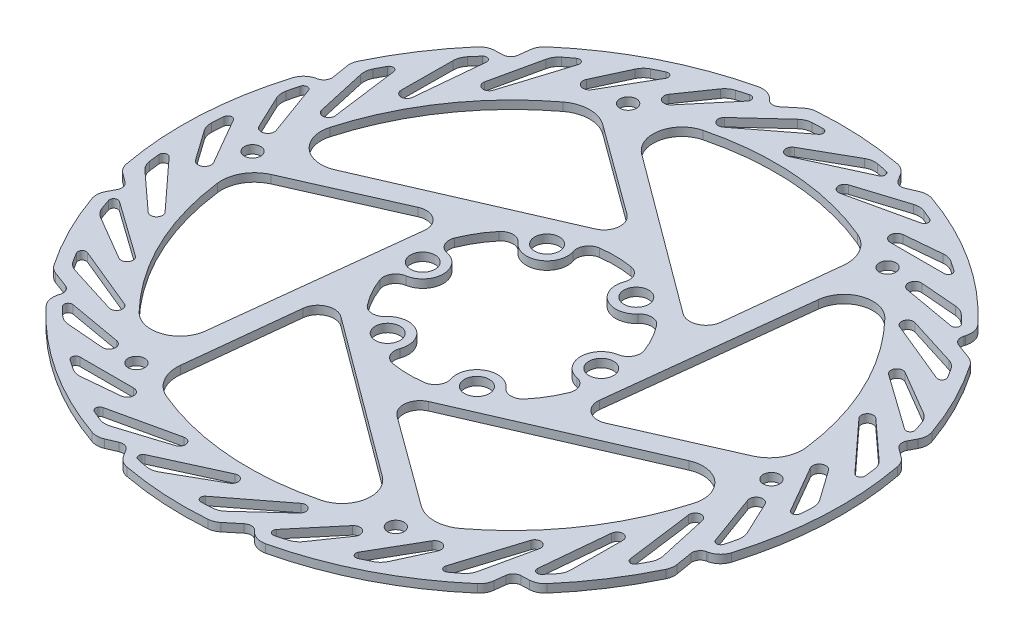
SolidWorks part; units mm, degrees
material "1060 Alloy"
ref_plane "Front Plane" through (0, 0, 0) normal (0, 0, 1) x (1, 0, 0)
ref_plane "Top Plane" through (0, 0, 0) normal (0, 1, 0) x (1, 0, 0)
ref_plane "Right Plane" through (0, 0, 0) normal (1, 0, 0) x (0, 0, -1)
sketch "Sketch5" plane through (0, 0, 0) normal (0, 1, 0) x (1, 0, 0)
  circle A0 centre (0, 0) radius 80
  dimension "D1" = 160
extrude "Boss-Extrude4" add sketch "Sketch5" along normal blind 2
sketch "Sketch7" plane through (0, 0, 0) normal (0, 1, 0) x (1, 0, 0)
  circle A0 centre (-30.3929, 58.5856) radius 2
  circle A1 centre (35.5401, 55.6138) radius 2
  circle A2 centre (65.9331, -2.9718) radius 2
  circle A3 centre (30.3929, -58.5856) radius 2
  circle A4 centre (-35.5401, -55.6138) radius 2
  circle A5 centre (-65.9331, 2.9718) radius 2
  dimension "D1" = 4
  dimension "D2" = 66
  dimension "D3" = 6
extrude "Cut-Extrude7" cut sketch "Sketch7" along a picked direction on the side of the normal through all
sketch "Sketch8" plane through (0, 0, 0) normal (0, 1, 0) x (1, 0, 0)
  circle A0 centre (-10.7073, 19.2186) radius 3
  circle A1 centre (11.2902, 18.8821) radius 3
  circle A2 centre (21.9974, -0.3365) radius 3
  circle A3 centre (10.7073, -19.2186) radius 3
  circle A4 centre (-11.2902, -18.8821) radius 3
  circle A5 centre (-21.9974, 0.3365) radius 3
  dimension "D1" = 6
  dimension "D2" = 22
  dimension "D3" = 6
extrude "Cut-Extrude11" cut sketch "Sketch8" along normal blind 2
sketch "Sketch9" plane through (0, 0, 0) normal (0, 1, 0) x (1, 0, 0)
  line L0 (-18.1578, 49.6272) -> (20.4623, 21.0635)
  line L1 (26.8178, 23.8504) -> (29.7187, 50.7393)
  line L2 (33.8995, 40.5387) -> (28.4727, -7.1891)
  line L3 (34.064, -11.2997) -> (58.8009, -0.3675)
  line L4 (52.0573, -9.0885) -> (8.0104, -28.2526)
  line L5 (7.2462, -35.1501) -> (29.0822, -51.1068)
  line L6 (18.1578, -49.6272) -> (-20.4623, -21.0635)
  line L7 (-26.8178, -23.8504) -> (-29.7187, -50.7393)
  line L8 (-33.8995, -40.5387) -> (-28.4727, 7.1891)
  line L9 (-34.064, 11.2997) -> (-58.8009, 0.3675)
  line L10 (-52.0573, 9.0885) -> (-8.0104, 28.2526)
  line L11 (-7.2462, 35.1501) -> (-29.0822, 51.1068)
  arc A0 (24.8741, 58.9685) -> (-15.7141, 62.0409) centre (0, 0) ccw
  arc A1 (-15.7141, 62.0409) -> (-18.1578, 49.6272) centre (-13.9953, 55.2551) ccw
  arc A2 (29.7187, 50.7393) -> (24.8741, 58.9685) centre (21.7648, 51.5974) ccw
  arc A3 (26.8178, 23.8504) -> (20.4623, 21.0635) centre (22.8409, 24.2795) cw
  arc A4 (45.8719, 44.6292) -> (33.8995, 40.5387) centre (40.8547, 39.7479) ccw
  arc A5 (63.5052, 7.9426) -> (45.8719, 44.6292) centre (0, 0) ccw
  arc A6 (58.8009, -0.3675) -> (63.5052, 7.9426) centre (55.5671, 6.9498) ccw
  arc A7 (34.064, -11.2997) -> (28.4727, -7.1891) centre (32.4471, -7.641) cw
  arc A8 (61.586, -17.4116) -> (52.0573, -9.0885) centre (54.85, -15.5072) ccw
  arc A9 (38.6311, -51.0258) -> (61.586, -17.4116) centre (0, 0) ccw
  arc A10 (29.0822, -51.1068) -> (38.6311, -51.0258) centre (33.8023, -44.6476) ccw
  arc A11 (7.2462, -35.1501) -> (8.0104, -28.2526) centre (9.6062, -31.9205) cw
  arc A12 (15.7141, -62.0409) -> (18.1578, -49.6272) centre (13.9953, -55.2551) ccw
  arc A13 (-24.8741, -58.9685) -> (15.7141, -62.0409) centre (0, 0) ccw
  arc A14 (-29.7187, -50.7393) -> (-24.8741, -58.9685) centre (-21.7648, -51.5974) ccw
  arc A15 (-26.8178, -23.8504) -> (-20.4623, -21.0635) centre (-22.8409, -24.2795) cw
  arc A16 (-45.8719, -44.6292) -> (-33.8995, -40.5387) centre (-40.8547, -39.7479) ccw
  arc A17 (-63.5052, -7.9426) -> (-45.8719, -44.6292) centre (0, 0) ccw
  arc A18 (-58.8009, 0.3675) -> (-63.5052, -7.9426) centre (-55.5671, -6.9498) ccw
  arc A19 (-34.064, 11.2997) -> (-28.4727, 7.1891) centre (-32.4471, 7.641) cw
  arc A20 (-61.586, 17.4116) -> (-52.0573, 9.0885) centre (-54.85, 15.5072) ccw
  arc A21 (-38.6311, 51.0258) -> (-61.586, 17.4116) centre (0, 0) ccw
  arc A22 (-29.0822, 51.1068) -> (-38.6311, 51.0258) centre (-33.8023, 44.6476) ccw
  arc A23 (-7.2462, 35.1501) -> (-8.0104, 28.2526) centre (-9.6062, 31.9205) cw
  dimension "D1" = 128
  dimension "D2" = 7
  dimension "D3" = 8
  dimension "D4" = 4
  dimension "D5" = 6
extrude "Cut-Extrude12" cut sketch "Sketch9" along normal blind 2
sketch "Sketch10" plane through (0, 0, 0) normal (0, 1, 0) x (1, 0, 0)
  arc A0 (4.309, 24.6258) -> (-3.5537, 24.7461) centre (0, 0) ccw
  arc A1 (6.6038, 20.625) -> (15.0435, 15.5786) centre (11.2902, 18.8821) ccw
  arc A2 (6.6038, 20.625) -> (4.309, 24.6258) centre (3.7919, 21.6707) ccw
  arc A3 (19.6539, 15.4507) -> (15.0435, 15.5786) centre (17.2955, 13.5966) ccw
  arc A4 (21.1637, 4.5935) -> (23.4811, 8.5812) centre (20.6634, 7.5514) ccw
  arc A5 (21.1637, 4.5935) -> (21.0132, -5.2387) centre (21.9974, -0.3365) ccw
  arc A6 (23.2076, -9.2955) -> (21.0132, -5.2387) centre (20.4227, -8.18) ccw
  arc A7 (14.5599, -16.0315) -> (19.1721, -16.0447) centre (16.8714, -14.1193) ccw
  arc A8 (14.5599, -16.0315) -> (5.9698, -20.8174) centre (10.7073, -19.2186) ccw
  arc A9 (3.5537, -24.7461) -> (5.9698, -20.8174) centre (3.1272, -21.7766) ccw
  arc A10 (-6.6038, -20.625) -> (-4.309, -24.6258) centre (-3.7919, -21.6707) ccw
  arc A11 (-6.6038, -20.625) -> (-15.0435, -15.5786) centre (-11.2902, -18.8821) ccw
  arc A12 (-19.6539, -15.4507) -> (-15.0435, -15.5786) centre (-17.2955, -13.5966) ccw
  arc A13 (-21.1637, -4.5935) -> (-23.4811, -8.5812) centre (-20.6634, -7.5514) ccw
  arc A14 (-21.1637, -4.5935) -> (-21.0132, 5.2387) centre (-21.9974, 0.3365) ccw
  arc A15 (-23.2076, 9.2955) -> (-21.0132, 5.2387) centre (-20.4227, 8.18) ccw
  arc A16 (-14.5599, 16.0315) -> (-19.1721, 16.0447) centre (-16.8714, 14.1193) ccw
  arc A17 (-14.5599, 16.0315) -> (-5.9698, 20.8174) centre (-10.7073, 19.2186) ccw
  arc A18 (-3.5537, 24.7461) -> (-5.9698, 20.8174) centre (-3.1272, 21.7766) ccw
  arc A19 (-19.1721, 16.0447) -> (-23.2076, 9.2955) centre (0, 0) ccw
  arc A20 (-23.4811, -8.5812) -> (-19.6539, -15.4507) centre (0, 0) ccw
  arc A21 (-4.309, -24.6258) -> (3.5537, -24.7461) centre (0, 0) ccw
  arc A22 (19.1721, -16.0447) -> (23.2076, -9.2955) centre (0, 0) ccw
  arc A23 (23.4811, 8.5812) -> (19.6539, 15.4507) centre (0, 0) ccw
  dimension "D1" = 50
  dimension "D2" = 10
  dimension "D3" = 3
  dimension "D4" = 6
extrude "Cut-Extrude13" cut sketch "Sketch10" along normal blind 2
sketch "Sketch11" plane through (0, 0, 0) normal (0, 1, 0) x (1, 0, 0)
  line L0 (-43.6685, -61.2018) -> (-30.6118, -61.2018)
  line L1 (-39.3689, -65.2195) -> (-30.4643, -64.395)
  line L2 (-55.4861, -51.0375) -> (-42.6278, -53.3048)
  line L3 (-51.9496, -55.7408) -> (-43.037, -56.4751)
  line L4 (-64.6876, -38.3442) -> (-49.4725, -44.6227)
  line L5 (-62.4068, -43.5967) -> (-50.4598, -47.3465)
  line L6 (-71.5531, -23.7165) -> (-58.1404, -33.2567)
  line L7 (-70.5123, -29.3475) -> (-59.7151, -35.6886)
  line L8 (-74.9029, -8.312) -> (-63.7667, -20.4324)
  line L9 (-75.0556, -14.0363) -> (-65.8127, -22.4838)
  line L10 (-49.6836, 57.9819) -> (-52.3778, 45.7535)
  line L11 (-44.6499, 60.7118) -> (-49.5783, 45.0074)
  line L12 (-56.3157, 50.1086) -> (-57.8713, 33.7227)
  line L13 (-60.6718, 46.3917) -> (-60.7648, 33.8705)
  line L14 (-68.9592, 32.2475) -> (-66.2332, 20.0262)
  line L15 (-65.5508, 36.849) -> (-63.3806, 20.5331)
  line L16 (-71.9428, 22.5336) -> (-67.4772, 10.2643)
  line L17 (-74.2477, 17.1192) -> (-70.4273, 9.0336)
  line L18 (-74.8366, 7.2171) -> (-68.3082, -4.0903)
  line L19 (-76.1662, 1.4848) -> (-70.9998, -5.8147)
  line L20 (25.372, 72.0182) -> (13.4348, 68.2373)
  line L21 (30.253, 69.0238) -> (14.1884, 65.4398)
  line L22 (15.2375, 73.8251) -> (0.269, 66.9794)
  line L23 (9.8405, 75.7392) -> (-1.0497, 69.5591)
  line L24 (-6.5525, 75.8442) -> (-15.7734, 67.3727)
  line L25 (-0.8633, 75.1932) -> (-13.9081, 65.1558)
  line L26 (-16.4567, 73.5711) -> (-24.8494, 63.5691)
  line L27 (-22.2982, 72.86) -> (-27.3904, 65.5087)
  line L28 (-31.1681, 68.4189) -> (-37.6964, 57.1115)
  line L29 (-36.7973, 66.7043) -> (-40.5356, 58.5803)
  line L30 (75.0556, 14.0363) -> (65.8127, 22.4838)
  line L31 (74.9029, 8.312) -> (63.7667, 20.4324)
  line L32 (71.5531, 23.7165) -> (58.1404, 33.2567)
  line L33 (70.5123, 29.3475) -> (59.7151, 35.6886)
  line L34 (62.4068, 43.5967) -> (50.4598, 47.3465)
  line L35 (64.6876, 38.3442) -> (49.4725, 44.6227)
  line L36 (55.4861, 51.0375) -> (42.6278, 53.3048)
  line L37 (51.9496, 55.7408) -> (43.037, 56.4751)
  line L38 (43.6685, 61.2018) -> (30.6118, 61.2018)
  line L39 (39.3689, 65.2195) -> (30.4643, 64.395)
  line L40 (49.6836, -57.9819) -> (52.3778, -45.7535)
  line L41 (44.6499, -60.7118) -> (49.5783, -45.0074)
  line L42 (56.3157, -50.1086) -> (57.8713, -33.7227)
  line L43 (60.6718, -46.3917) -> (60.7648, -33.8705)
  line L44 (68.9592, -32.2475) -> (66.2332, -20.0262)
  line L45 (65.5508, -36.849) -> (63.3806, -20.5331)
  line L46 (71.9428, -22.5336) -> (67.4772, -10.2643)
  line L47 (74.2477, -17.1192) -> (70.4273, -9.0336)
  line L48 (74.8366, -7.2171) -> (68.3082, 4.0903)
  line L49 (76.1662, -1.4848) -> (70.9998, 5.8147)
  line L50 (-25.372, -72.0182) -> (-13.4348, -68.2373)
  line L51 (-30.253, -69.0238) -> (-14.1884, -65.4398)
  line L52 (-15.2375, -73.8251) -> (-0.269, -66.9794)
  line L53 (-9.8405, -75.7392) -> (1.0497, -69.5591)
  line L54 (6.5525, -75.8442) -> (15.7734, -67.3727)
  line L55 (0.8633, -75.1932) -> (13.9081, -65.1558)
  line L56 (16.4567, -73.5711) -> (24.8494, -63.5691)
  line L57 (22.2982, -72.86) -> (27.3904, -65.5087)
  line L58 (31.1681, -68.4189) -> (37.6964, -57.1115)
  line L59 (36.7973, -66.7043) -> (40.5356, -58.5803)
  arc A0 (-64.6876, -38.3442) -> (-65.9252, -39.7853) centre (-65.069, -39.2686) ccw
  arc A1 (-65.9252, -39.7853) -> (-64.5628, -41.96) centre (0, 0) ccw
  arc A2 (-43.6685, -61.2018) -> (-44.2431, -63.0202) centre (-43.6685, -62.2018) ccw
  arc A3 (-44.2431, -63.0202) -> (-41.9152, -64.5919) centre (0, 0) ccw
  arc A4 (-62.4068, -43.5967) -> (-64.5628, -41.96) centre (-61.2089, -39.7803) cw
  arc A5 (-49.4725, -44.6227) -> (-50.4598, -47.3465) centre (-50.0256, -45.963) cw
  arc A6 (-58.1404, -33.2567) -> (-59.7151, -35.6886) centre (-58.9808, -34.4383) cw
  arc A7 (-71.5531, -23.7165) -> (-73.0832, -24.8423) centre (-72.1327, -24.5314) ccw
  arc A8 (-70.5123, -29.3475) -> (-72.245, -27.2677) centre (-68.4867, -25.8983) cw
  arc A9 (-73.0832, -24.8423) -> (-72.245, -27.2677) centre (0.1021, -0.9066) ccw
  arc A10 (-63.7667, -20.4324) -> (-65.8127, -22.4838) centre (-64.8344, -21.4134) cw
  arc A11 (-74.9029, -8.312) -> (-76.6336, -9.095) centre (-75.6392, -8.9886) ccw
  arc A12 (-75.0556, -14.0363) -> (-76.3179, -11.6418) centre (-72.357, -11.0837) cw
  arc A13 (-76.6336, -9.095) -> (-76.3179, -11.6418) centre (-0.0711, -0.8985) ccw
  arc A14 (-39.3689, -65.2195) -> (-41.9152, -64.5919) centre (-39.7377, -61.2365) cw
  arc A15 (-30.4643, -64.395) -> (-30.6118, -61.2018) centre (-30.6118, -62.8018) ccw
  arc A16 (-51.9496, -55.7408) -> (-54.3481, -54.6806) centre (-51.6211, -51.7543) cw
  arc A17 (-43.037, -56.4751) -> (-42.6278, -53.3048) centre (-42.9056, -54.8805) ccw
  arc A18 (-56.3677, -52.7286) -> (-54.3481, -54.6806) centre (-1.8535, 1.6515) ccw
  arc A19 (-55.4861, -51.0375) -> (-56.3677, -52.7286) centre (-55.6598, -52.0223) ccw
  arc A20 (-44.6499, 60.7118) -> (-46.1933, 61.8191) centre (-45.604, 61.0112) ccw
  arc A21 (-46.1933, 61.8191) -> (-48.241, 60.2724) centre (-0.8137, -0.3877) ccw
  arc A22 (-49.6836, 57.9819) -> (-48.241, 60.2724) centre (-45.7773, 57.1212) cw
  arc A23 (-49.5783, 45.0074) -> (-52.3778, 45.7535) centre (-50.9618, 45.4416) cw
  arc A24 (-57.8713, 33.7227) -> (-60.7648, 33.8705) centre (-59.3148, 33.8597) cw
  arc A25 (-60.6718, 46.3917) -> (-59.737, 48.9321) centre (-56.6719, 46.362) cw
  arc A26 (-58.0556, 50.8708) -> (-59.737, 48.9321) centre (-0.7341, -0.5417) ccw
  arc A27 (-56.3157, 50.1086) -> (-58.0556, 50.8708) centre (-57.3112, 50.2031) ccw
  arc A28 (-63.3806, 20.5331) -> (-66.2332, 20.0262) centre (-64.8179, 20.3419) cw
  arc A29 (-65.5508, 36.849) -> (-67.4177, 37.2002) centre (-66.5421, 36.7171) ccw
  arc A30 (-67.4177, 37.2002) -> (-68.6198, 34.933) centre (0, 0) ccw
  arc A31 (-68.9592, 32.2475) -> (-68.6198, 34.933) centre (-65.0552, 33.1183) cw
  arc A32 (-73.8481, 22.4516) -> (-74.5289, 19.7265) centre (0.5035, 2.4309) ccw
  arc A33 (-71.9428, 22.5336) -> (-73.8481, 22.4516) centre (-72.8825, 22.1916) ccw
  arc A34 (-74.2477, 17.1192) -> (-74.5289, 19.7265) centre (-70.6311, 18.8281) cw
  arc A35 (-70.4273, 9.0336) -> (-67.4772, 10.2643) centre (-68.9807, 9.7171) ccw
  arc A36 (-70.9998, -5.8147) -> (-68.3082, -4.0903) centre (-69.6938, -4.8903) ccw
  arc A37 (-76.6987, 6.8055) -> (-76.8958, 4.0036) centre (0, 0) ccw
  arc A38 (-74.8366, 7.2171) -> (-76.6987, 6.8055) centre (-75.7026, 6.7171) ccw
  arc A39 (-76.1662, 1.4848) -> (-76.8958, 4.0036) centre (-72.9013, 3.7956) cw
  arc A40 (30.253, 69.0238) -> (30.4402, 70.9141) centre (30.0353, 69.9998) ccw
  arc A41 (30.4402, 70.9141) -> (28.0769, 71.9141) centre (-0.7426, 0.5108) ccw
  arc A42 (25.372, 72.0182) -> (28.0769, 71.9141) centre (26.5798, 68.2049) cw
  arc A43 (14.1884, 65.4398) -> (13.4348, 68.2373) centre (13.8726, 66.855) cw
  arc A44 (0.269, 66.9794) -> (-1.0497, 69.5591) centre (-0.334, 68.298) cw
  arc A45 (9.8405, 75.7392) -> (12.508, 76.1998) centre (11.8148, 72.2603) cw
  arc A46 (15.0276, 75.713) -> (12.508, 76.1998) centre (-0.8362, 0.3649) ccw
  arc A47 (15.2375, 73.8251) -> (15.0276, 75.713) centre (14.8215, 74.7345) ccw
  arc A48 (-13.9081, 65.1558) -> (-15.7734, 67.3727) centre (-14.7924, 66.3049) cw
  arc A49 (-0.8633, 75.1932) -> (-1.4925, 76.9855) centre (-1.4731, 75.9857) ccw
  arc A50 (-1.4925, 76.9855) -> (-4.057, 76.893) centre (0, 0) ccw
  arc A51 (-6.5525, 75.8442) -> (-4.057, 76.893) centre (-3.8463, 72.8986) cw
  arc A52 (-17.4804, 75.1802) -> (-20.1808, 74.4072) centre (2.357, 0.7794) ccw
  arc A53 (-16.4567, 73.5711) -> (-17.4804, 75.1802) centre (-17.2228, 74.2139) ccw
  arc A54 (-22.2982, 72.86) -> (-20.1808, 74.4072) centre (-19.01, 70.5823) cw
  arc A55 (-27.3904, 65.5087) -> (-24.8494, 63.5691) centre (-26.0751, 64.5976) ccw
  arc A56 (-40.5356, 58.5803) -> (-37.6964, 57.1115) centre (-39.0821, 57.9115) ccw
  arc A57 (-32.4556, 69.8257) -> (-34.9807, 68.5956) centre (0, 0) ccw
  arc A58 (-31.1681, 68.4189) -> (-32.4556, 69.8257) centre (-32.0341, 68.9189) ccw
  arc A59 (-36.7973, 66.7043) -> (-34.9807, 68.5956) centre (-33.1635, 65.0322) cw
  arc A60 (74.9029, 8.312) -> (76.6336, 9.095) centre (75.6392, 8.9886) ccw
  arc A61 (76.6336, 9.095) -> (76.3179, 11.6418) centre (0.0711, 0.8985) ccw
  arc A62 (75.0556, 14.0363) -> (76.3179, 11.6418) centre (72.357, 11.0837) cw
  arc A63 (63.7667, 20.4324) -> (65.8127, 22.4838) centre (64.8344, 21.4134) cw
  arc A64 (58.1404, 33.2567) -> (59.7151, 35.6886) centre (58.9808, 34.4383) cw
  arc A65 (70.5123, 29.3475) -> (72.245, 27.2677) centre (68.4867, 25.8983) cw
  arc A66 (73.0832, 24.8423) -> (72.245, 27.2677) centre (-0.1021, 0.9066) ccw
  arc A67 (71.5531, 23.7165) -> (73.0832, 24.8423) centre (72.1327, 24.5314) ccw
  arc A68 (49.4725, 44.6227) -> (50.4598, 47.3465) centre (50.0256, 45.963) cw
  arc A69 (64.6876, 38.3442) -> (65.9252, 39.7853) centre (65.069, 39.2686) ccw
  arc A70 (65.9252, 39.7853) -> (64.5628, 41.96) centre (0, 0) ccw
  arc A71 (62.4068, 43.5967) -> (64.5628, 41.96) centre (61.2089, 39.7803) cw
  arc A72 (56.3677, 52.7286) -> (54.3481, 54.6806) centre (1.8535, -1.6515) ccw
  arc A73 (55.4861, 51.0375) -> (56.3677, 52.7286) centre (55.6598, 52.0223) ccw
  arc A74 (51.9496, 55.7408) -> (54.3481, 54.6806) centre (51.6211, 51.7543) cw
  arc A75 (43.037, 56.4751) -> (42.6278, 53.3048) centre (42.9056, 54.8805) ccw
  arc A76 (30.4643, 64.395) -> (30.6118, 61.2018) centre (30.6118, 62.8018) ccw
  arc A77 (44.2431, 63.0202) -> (41.9152, 64.5919) centre (0, 0) ccw
  arc A78 (43.6685, 61.2018) -> (44.2431, 63.0202) centre (43.6685, 62.2018) ccw
  arc A79 (39.3689, 65.2195) -> (41.9152, 64.5919) centre (39.7377, 61.2365) cw
  arc A80 (44.6499, -60.7118) -> (46.1933, -61.8191) centre (45.604, -61.0112) ccw
  arc A81 (46.1933, -61.8191) -> (48.241, -60.2724) centre (0.8137, 0.3877) ccw
  arc A82 (49.6836, -57.9819) -> (48.241, -60.2724) centre (45.7773, -57.1212) cw
  arc A83 (49.5783, -45.0074) -> (52.3778, -45.7535) centre (50.9618, -45.4416) cw
  arc A84 (57.8713, -33.7227) -> (60.7648, -33.8705) centre (59.3148, -33.8597) cw
  arc A85 (60.6718, -46.3917) -> (59.737, -48.9321) centre (56.6719, -46.362) cw
  arc A86 (58.0556, -50.8708) -> (59.737, -48.9321) centre (0.7341, 0.5417) ccw
  arc A87 (56.3157, -50.1086) -> (58.0556, -50.8708) centre (57.3112, -50.2031) ccw
  arc A88 (63.3806, -20.5331) -> (66.2332, -20.0262) centre (64.8179, -20.3419) cw
  arc A89 (65.5508, -36.849) -> (67.4177, -37.2002) centre (66.5421, -36.7171) ccw
  arc A90 (67.4177, -37.2002) -> (68.6198, -34.933) centre (0, 0) ccw
  arc A91 (68.9592, -32.2475) -> (68.6198, -34.933) centre (65.0552, -33.1183) cw
  arc A92 (73.8481, -22.4516) -> (74.5289, -19.7265) centre (-0.5035, -2.4309) ccw
  arc A93 (71.9428, -22.5336) -> (73.8481, -22.4516) centre (72.8825, -22.1916) ccw
  arc A94 (74.2477, -17.1192) -> (74.5289, -19.7265) centre (70.6311, -18.8281) cw
  arc A95 (70.4273, -9.0336) -> (67.4772, -10.2643) centre (68.9807, -9.7171) ccw
  arc A96 (70.9998, 5.8147) -> (68.3082, 4.0903) centre (69.6938, 4.8903) ccw
  arc A97 (76.6987, -6.8055) -> (76.8958, -4.0036) centre (0, 0) ccw
  arc A98 (74.8366, -7.2171) -> (76.6987, -6.8055) centre (75.7026, -6.7171) ccw
  arc A99 (76.1662, -1.4848) -> (76.8958, -4.0036) centre (72.9013, -3.7956) cw
  arc A100 (-30.253, -69.0238) -> (-30.4402, -70.9141) centre (-30.0353, -69.9998) ccw
  arc A101 (-30.4402, -70.9141) -> (-28.0769, -71.9141) centre (0.7426, -0.5108) ccw
  arc A102 (-25.372, -72.0182) -> (-28.0769, -71.9141) centre (-26.5798, -68.2049) cw
  arc A103 (-14.1884, -65.4398) -> (-13.4348, -68.2373) centre (-13.8726, -66.855) cw
  arc A104 (-0.269, -66.9794) -> (1.0497, -69.5591) centre (0.334, -68.298) cw
  arc A105 (-9.8405, -75.7392) -> (-12.508, -76.1998) centre (-11.8148, -72.2603) cw
  arc A106 (-15.0276, -75.713) -> (-12.508, -76.1998) centre (0.8362, -0.3649) ccw
  arc A107 (-15.2375, -73.8251) -> (-15.0276, -75.713) centre (-14.8215, -74.7345) ccw
  arc A108 (13.9081, -65.1558) -> (15.7734, -67.3727) centre (14.7924, -66.3049) cw
  arc A109 (0.8633, -75.1932) -> (1.4925, -76.9855) centre (1.4731, -75.9857) ccw
  arc A110 (1.4925, -76.9855) -> (4.057, -76.893) centre (0, 0) ccw
  arc A111 (6.5525, -75.8442) -> (4.057, -76.893) centre (3.8463, -72.8986) cw
  arc A112 (17.4804, -75.1802) -> (20.1808, -74.4072) centre (-2.357, -0.7794) ccw
  arc A113 (16.4567, -73.5711) -> (17.4804, -75.1802) centre (17.2228, -74.2139) ccw
  arc A114 (22.2982, -72.86) -> (20.1808, -74.4072) centre (19.01, -70.5823) cw
  arc A115 (27.3904, -65.5087) -> (24.8494, -63.5691) centre (26.0751, -64.5976) ccw
  arc A116 (40.5356, -58.5803) -> (37.6964, -57.1115) centre (39.0821, -57.9115) ccw
  arc A117 (32.4556, -69.8257) -> (34.9807, -68.5956) centre (0, 0) ccw
  arc A118 (31.1681, -68.4189) -> (32.4556, -69.8257) centre (32.0341, -68.9189) ccw
  arc A119 (36.7973, -66.7043) -> (34.9807, -68.5956) centre (33.1635, -65.0322) cw
  dimension "D1" = 154
  dimension "D2" = 1
  dimension "D3" = 4
  dimension "D4" = 1.45
  dimension "D5" = 1
  dimension "D6" = 4
  dimension "D7" = 1.45
  dimension "D8" = 1
  dimension "D9" = 4
  dimension "D10" = 1.45
  dimension "D11" = 1
  dimension "D12" = 4
  dimension "D13" = 1.6
  dimension "D14" = 1
  dimension "D15" = 4
  dimension "D16" = 1.6
  dimension "D17" = 6
extrude "Cut-Extrude14" cut sketch "Sketch11" along normal blind 2
sketch "Sketch12" plane through (0, 0, 0) normal (0, 1, 0) x (1, 0, 0)
  line L0 (-57.7635, 53.5579) -> (-55.8273, 53.6288)
  line L1 (-53.6016, 58.0291) -> (-53.9144, 55.3918)
  line L2 (-72.4118, 32.3371) -> (-71.7525, 28.362)
  line L3 (-73.6145, 26.0076) -> (-73.2747, 26.0862)
  line L4 (23.4539, 75.4349) -> (21.0136, 74.3871)
  line L5 (17.5008, 76.8036) -> (18.5302, 75.1623)
  line L6 (-14.284, 76.7558) -> (-14.046, 76.5008)
  line L7 (-8.2012, 78.879) -> (-11.3141, 76.3205)
  line L8 (77.0555, 17.4057) -> (74.9279, 18.9953)
  line L9 (75.2643, 23.2457) -> (74.3575, 21.5335)
  line L10 (59.3305, 50.7482) -> (59.2287, 50.4146)
  line L11 (64.2107, 46.5419) -> (60.4385, 47.9585)
  line L12 (53.6016, -58.0291) -> (53.9144, -55.3918)
  line L13 (57.7635, -53.5579) -> (55.8273, -53.6288)
  line L14 (73.6145, -26.0076) -> (73.2747, -26.0862)
  line L15 (72.4118, -32.3371) -> (71.7525, -28.362)
  line L16 (-23.4539, -75.4349) -> (-21.0136, -74.3871)
  line L17 (-17.5008, -76.8036) -> (-18.5302, -75.1623)
  line L18 (14.284, -76.7558) -> (14.046, -76.5008)
  line L19 (8.2012, -78.879) -> (11.3141, -76.3205)
  line L20 (-77.0555, -17.4057) -> (-74.9279, -18.9953)
  line L21 (-75.2643, -23.2457) -> (-74.3575, -21.5335)
  line L22 (-59.3305, -50.7482) -> (-59.2287, -50.4146)
  line L23 (-64.2107, -46.5419) -> (-60.4385, -47.9585)
  arc A1 (-76.5396, 23.2743) -> (-72.0692, 34.728) centre (0, 0) cw
  arc A2 (-71.7525, 28.362) -> (-73.2747, 26.0862) centre (-73.7256, 28.0347) cw
  arc A3 (-53.9144, 55.3918) -> (-55.8273, 53.6288) centre (-55.9004, 55.6274) cw
  arc A4 (-60.6497, 52.169) -> (-52.2415, 60.5874) centre (0, 0) cw
  arc A5 (14.8548, 78.6087) -> (26.3495, 75.5361) centre (0, 0) cw
  arc A6 (26.3495, 75.5361) -> (23.4539, 75.4349) centre (25.032, 71.7593) ccw
  arc A7 (-52.2415, 60.5874) -> (-53.6016, 58.0291) centre (-49.6294, 57.558) ccw
  arc A8 (-57.7635, 53.5579) -> (-60.6497, 52.169) centre (-57.6173, 49.5606) ccw
  arc A9 (-72.0692, 34.728) -> (-72.4118, 32.3371) centre (-68.4657, 32.9916) ccw
  arc A10 (-73.6145, 26.0076) -> (-76.5396, 23.2743) centre (-72.7126, 22.1106) ccw
  arc A11 (21.0136, 74.3871) -> (18.5302, 75.1623) centre (20.2245, 76.2249) cw
  arc A12 (17.5008, 76.8036) -> (14.8548, 78.6087) centre (14.1121, 74.6783) ccw
  arc A13 (-18.1136, 77.9224) -> (-5.9593, 79.7777) centre (0, 0) cw
  arc A14 (-14.284, 76.7558) -> (-18.1136, 77.9224) centre (-17.208, 74.0263) ccw
  arc A15 (-11.3141, 76.3205) -> (-14.046, 76.5008) centre (-12.584, 77.8656) cw
  arc A16 (-5.9593, 79.7777) -> (-8.2012, 78.879) centre (-5.6613, 75.7888) ccw
  arc A17 (75.5046, 26.4397) -> (78.5909, 14.9488) centre (0, 0) cw
  arc A18 (78.5909, 14.9488) -> (77.0555, 17.4057) centre (74.6614, 14.2013) ccw
  arc A19 (74.9279, 18.9953) -> (74.3575, 21.5335) centre (76.125, 20.5975) cw
  arc A20 (75.2643, 23.2457) -> (75.5046, 26.4397) centre (71.7294, 25.1177) ccw
  arc A21 (58.4259, 54.6481) -> (66.1099, 45.0498) centre (0, 0) cw
  arc A22 (59.3305, 50.7482) -> (58.4259, 54.6481) centre (55.5046, 51.9157) ccw
  arc A23 (60.4385, 47.9585) -> (59.2287, 50.4146) centre (61.1416, 49.8309) cw
  arc A24 (66.1099, 45.0498) -> (64.2107, 46.5419) centre (62.8044, 42.7973) ccw
  arc A25 (60.6497, -52.169) -> (52.2415, -60.5874) centre (0, 0) cw
  arc A26 (52.2415, -60.5874) -> (53.6016, -58.0291) centre (49.6294, -57.558) ccw
  arc A27 (53.9144, -55.3918) -> (55.8273, -53.6288) centre (55.9004, -55.6274) cw
  arc A28 (57.7635, -53.5579) -> (60.6497, -52.169) centre (57.6173, -49.5606) ccw
  arc A29 (76.5396, -23.2743) -> (72.0692, -34.728) centre (0, 0) cw
  arc A30 (73.6145, -26.0076) -> (76.5396, -23.2743) centre (72.7126, -22.1106) ccw
  arc A31 (71.7525, -28.362) -> (73.2747, -26.0862) centre (73.7256, -28.0347) cw
  arc A32 (72.0692, -34.728) -> (72.4118, -32.3371) centre (68.4657, -32.9916) ccw
  arc A33 (-14.8548, -78.6087) -> (-26.3495, -75.5361) centre (0, 0) cw
  arc A34 (-26.3495, -75.5361) -> (-23.4539, -75.4349) centre (-25.032, -71.7593) ccw
  arc A35 (-21.0136, -74.3871) -> (-18.5302, -75.1623) centre (-20.2245, -76.2249) cw
  arc A36 (-17.5008, -76.8036) -> (-14.8548, -78.6087) centre (-14.1121, -74.6783) ccw
  arc A37 (18.1136, -77.9224) -> (5.9593, -79.7777) centre (0, 0) cw
  arc A38 (14.284, -76.7558) -> (18.1136, -77.9224) centre (17.208, -74.0263) ccw
  arc A39 (11.3141, -76.3205) -> (14.046, -76.5008) centre (12.584, -77.8656) cw
  arc A40 (5.9593, -79.7777) -> (8.2012, -78.879) centre (5.6613, -75.7888) ccw
  arc A41 (-75.5046, -26.4397) -> (-78.5909, -14.9488) centre (0, 0) cw
  arc A42 (-78.5909, -14.9488) -> (-77.0555, -17.4057) centre (-74.6614, -14.2013) ccw
  arc A43 (-74.9279, -18.9953) -> (-74.3575, -21.5335) centre (-76.125, -20.5975) cw
  arc A44 (-75.2643, -23.2457) -> (-75.5046, -26.4397) centre (-71.7294, -25.1177) ccw
  arc A45 (-58.4259, -54.6481) -> (-66.1099, -45.0498) centre (0, 0) cw
  arc A46 (-59.3305, -50.7482) -> (-58.4259, -54.6481) centre (-55.5046, -51.9157) ccw
  arc A47 (-60.4385, -47.9585) -> (-59.2287, -50.4146) centre (-61.1416, -49.8309) cw
  arc A48 (-66.1099, -45.0498) -> (-64.2107, -46.5419) centre (-62.8044, -42.7973) ccw
  dimension "D1" = 2
  dimension "D2" = 4
  dimension "D3" = 4
  dimension "D4" = 4
  dimension "D5" = 4
  dimension "D6" = 6
extrude "Cut-Extrude15" cut sketch "Sketch12" along normal blind 2
